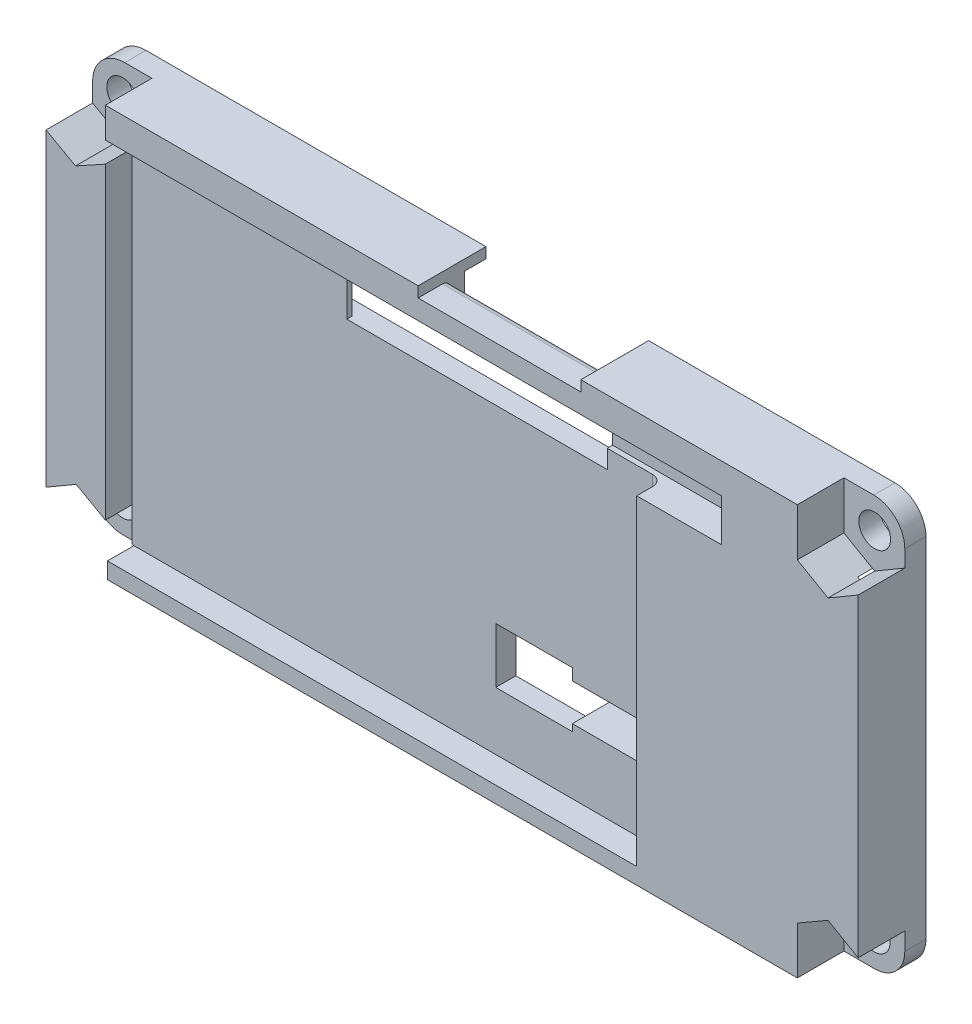
SolidWorks part; units mm, degrees
ref_plane "前视基准面" through (0, 0, 0) normal (0, 0, 1) x (1, 0, 0)
ref_plane "上视基准面" through (0, 0, 0) normal (0, 1, 0) x (1, 0, 0)
ref_plane "右视基准面" through (0, 0, 0) normal (1, 0, 0) x (0, 0, -1)
other "Configuration Table"
sketch "草图1" plane through (0, 0, 0) normal (0, 0, 1) x (1, 0, 0)
  line L0 (-73.5331, 38.5954) -> (-64.5685, 38.5954)
  line L1 (-2.794, 38.5954) -> (-73.5331, 38.5954) construction
  line L2 (-64.5685, 38.5954) -> (-64.5685, 29.9954)
  line L3 (-64.5685, 29.9954) -> (-75.2685, 29.9954)
  line L4 (-75.2685, 29.9954) -> (-75.2685, 9.1857)
  line L5 (-75.2685, 9.1857) -> (-68.5685, 9.1857)
  line L6 (-68.5685, 9.1857) -> (-68.5685, -0.1143)
  line L7 (-73.7871, -0.1143) -> (-2.715, -0.1143) construction
  line L8 (-68.5685, -0.1143) -> (-73.7871, -0.1143)
  line L9 (-76.5685, 2.667) -> (-76.5685, 35.5601)
  line L10 (-20.3702, 38.5954) -> (-2.794, 38.5954)
  line L11 (0.1298, 35.6715) -> (0.1298, 2.7305)
  line L12 (-2.715, -0.1143) -> (-29.3702, -0.1143)
  line L13 (-29.3702, -0.1143) -> (-29.3702, 7.5643)
  line L14 (-29.3702, 16.2857) -> (-25.7194, 16.2857)
  line L15 (-25.7194, 16.2857) -> (-25.7194, 22.5541)
  line L16 (-25.7194, 22.5541) -> (-20.6222, 22.5541)
  line L18 (-20.6222, 22.5541) -> (-20.6222, 16.1031)
  line L19 (-20.6222, 16.1031) -> (-21.974, 16.1031)
  line L21 (-21.974, 15.9031) -> (-21.974, 16.1031) construction
  line L22 (-21.974, 11.903) -> (-21.353, 11.903)
  line L23 (-21.353, 11.903) -> (-21.353, 11.0605)
  line L24 (-21.353, 2.6963) -> (-7.7837, 2.6963)
  line L25 (-7.7837, 2.6963) -> (-7.7837, 2.0822)
  line L26 (-7.7837, 2.0822) -> (-5.4155, 2.0822)
  line L27 (-5.4155, 2.0822) -> (-5.4155, 6.7277)
  line L28 (-5.4155, 6.7277) -> (-4.9394, 6.7277)
  line L29 (-4.9394, 6.7277) -> (-4.9394, 11.903)
  line L30 (-4.9394, 11.903) -> (-1.774, 11.903)
  line L31 (-1.774, 11.903) -> (-1.774, 30.5031)
  line L32 (-1.774, 29.9031) -> (-1.774, 12.003) construction
  line L33 (-3.774, 30.5031) -> (-1.774, 30.5031) construction
  line L34 (-5.774, 30.5031) -> (-5.774, 29.9954)
  line L35 (-5.774, 29.9954) -> (-20.3702, 29.9954)
  line L36 (-20.3702, 29.9954) -> (-20.3702, 38.5954)
  line L37 (-1.774, 12.003) -> (-20.374, 12.003) construction
  line L38 (-29.3702, 11.0605) -> (-29.3702, 16.2857)
  line L39 (-29.3702, 11.0605) -> (-21.353, 11.0605)
  line L41 (-29.3702, 7.5643) -> (-21.353, 7.5643)
  line L43 (-21.353, 7.5643) -> (-21.353, 2.6963)
  line L44 (-55.997, 25.7616) -> (-51.8906, 25.7616)
  line L45 (-55.997, 25.7616) -> (-55.997, 9.6668)
  line L46 (-55.997, 9.6668) -> (-51.8906, 9.6668)
  line L47 (-51.8906, 25.7616) -> (-51.8906, 9.6668)
  arc A0 (-73.7871, -0.1143) -> (-76.5685, 2.667) centre (-73.7871, 2.667) cw
  arc A1 (-76.5685, 35.5601) -> (-73.5331, 38.5954) centre (-73.5331, 35.5601) cw
  circle A2 centre (-73.7292, 35.7671) radius 1.5
  circle A3 centre (-73.7292, 2.755) radius 1.5
  arc A4 (-2.794, 38.5954) -> (0.1298, 35.6715) centre (-2.794, 35.6715) cw
  arc A5 (0.1298, 2.7305) -> (-2.715, -0.1143) centre (-2.715, 2.7305) cw
  arc A6 (-21.974, 16.1031) -> (-21.974, 11.903) centre (-21.974, 14.0031) ccw
  arc A7 (-1.774, 30.5031) -> (-5.774, 30.5031) centre (-3.774, 30.5031) ccw
  circle A8 centre (-21.974, 14.0031) radius 0.9 construction
  arc A9 (-3.5047, 29.8031) -> (-4.0433, 29.8031) centre (-3.774, 30.5031) ccw construction
  dimension "D1" = 8
  dimension "D2" = 9.3
  dimension "D3" = 1.3
  dimension "D4" = 8.6
  dimension "D5" = 12
  dimension "D6" = 0.1
  dimension "D7" = 0.1
  dimension "D8" = 20.5
  dimension "D9" = 29.5
extrude "凸台-拉伸1" add sketch "草图1" along normal blind 2
sketch "草图2" plane through (0, 0, 2) normal (0, 0, 1) x (1, 0, 0)
  line L0 (-20.3702, 38.5954) -> (-5.6189, 38.5954)
  line L1 (-2.794, 38.5954) -> (-20.3702, 38.5954) construction
  line L2 (-5.6189, 38.5954) -> (-5.6189, 34.0838)
  line L3 (-5.6189, 34.0838) -> (-2.7217, 32.4163)
  line L4 (-2.7217, 32.4163) -> (0.1298, 34.0838)
  line L5 (0.1298, 2.7305) -> (0.1298, 35.6715) construction
  line L6 (0.1298, 34.0838) -> (0.1298, 4.4128)
  line L7 (0.1298, 4.4128) -> (-2.7217, 6.054)
  line L8 (-2.7217, 6.054) -> (-5.6202, 4.3805)
  line L9 (-5.6202, 4.3805) -> (-5.6202, -0.1143)
  line L10 (-29.3702, -0.1143) -> (-2.715, -0.1143) construction
  line L11 (-5.6202, -0.1143) -> (-29.3702, -0.1143)
  line L12 (-29.3702, -0.1143) -> (-29.3702, 7.5643)
  line L13 (-29.3702, 7.5643) -> (-21.353, 7.5643)
  line L21 (-4.9394, 11.903) -> (-1.774, 11.903)
  line L22 (-1.774, 11.903) -> (-1.774, 30.5031)
  line L23 (-5.774, 30.5031) -> (-5.774, 29.9954)
  line L24 (-5.774, 29.9954) -> (-20.3702, 29.9954)
  line L25 (-20.3702, 29.9954) -> (-20.3702, 38.5954)
  line L26 (-21.353, 7.5643) -> (-20.7496, 7.5643)
  line L27 (-16.9173, 11.3967) -> (-16.9173, 11.903)
  line L28 (-16.9173, 11.903) -> (-4.9394, 11.903)
  line L29 (-70.8876, 38.5954) -> (-41.4286, 38.5954)
  line L30 (-64.5685, 38.5954) -> (-73.5331, 38.5954) construction
  line L31 (-2.794, 38.5954) -> (-73.5331, 38.5954) construction
  line L32 (-41.4286, 38.5954) -> (-41.4286, 35.0718)
  line L33 (-41.4286, 35.0718) -> (-56.2862, 35.0718)
  line L34 (-60.684, 30.6739) -> (-60.684, 29.9954)
  line L35 (-60.684, 29.9954) -> (-64.5685, 29.9954)
  line L36 (-64.5685, 29.9954) -> (-75.2685, 29.9954)
  line L37 (-75.2685, 29.9954) -> (-75.2685, 9.1857)
  line L38 (-75.2685, 9.1857) -> (-68.5685, 9.1857)
  line L39 (-68.5685, 9.1857) -> (-68.5685, 11.7982)
  line L40 (-68.5685, 11.7982) -> (-55.997, 11.7982)
  line L41 (-55.997, 25.7616) -> (-55.997, 9.6668) construction
  line L42 (-55.997, 11.7982) -> (-55.997, 25.7616)
  line L43 (-55.997, 25.7616) -> (-51.8906, 25.7616)
  line L44 (-51.8906, 25.7616) -> (-51.8906, 29.9954)
  line L45 (-51.8906, 29.9954) -> (-21.1628, 29.9954)
  line L46 (-21.1628, 29.9954) -> (-20.6222, 29.369)
  line L47 (-20.6222, 29.369) -> (-20.6222, 22.5541)
  line L48 (-20.6222, 22.5541) -> (-20.6222, 16.1031)
  line L49 (-20.6222, 16.1031) -> (-21.974, 16.1031)
  line L50 (-21.974, 11.903) -> (-21.353, 11.903)
  line L51 (-21.353, 11.0605) -> (-29.3702, 11.0605)
  line L52 (-29.3702, 11.0605) -> (-29.3702, 12.1441)
  line L53 (-29.3702, 16.2857) -> (-29.3702, 11.0605) construction
  line L54 (-29.3702, 12.1441) -> (-36.5981, 12.1441)
  line L55 (-36.5981, 12.1441) -> (-36.5981, -0.1143)
  line L56 (-73.7871, -0.1143) -> (-2.715, -0.1143) construction
  line L57 (-36.5981, -0.1143) -> (-70.7703, -0.1143)
  line L58 (-73.7871, -0.1143) -> (-68.5685, -0.1143) construction
  line L59 (-70.7703, -0.1143) -> (-70.7703, 4.5479)
  line L60 (-70.7703, 4.5479) -> (-73.7193, 6.209)
  line L61 (-73.7193, 6.209) -> (-76.5685, 4.5479)
  line L62 (-76.5685, 35.5601) -> (-76.5685, 2.667) construction
  line L63 (-76.5685, 4.5479) -> (-76.5685, 33.7734)
  line L64 (-76.5685, 33.7734) -> (-73.7871, 32.2146)
  line L65 (-73.7871, 32.2146) -> (-70.9685, 33.7734)
  line L66 (-70.9685, 34.5954) -> (-70.9685, 2.5954) construction
  line L67 (-70.9685, 33.7734) -> (-70.9685, 38.5954)
  line L68 (-70.9685, 38.5954) -> (-70.8876, 38.5954)
  line L69 (-21.353, 11.903) -> (-21.353, 11.0605)
  arc A0 (-1.774, 30.5031) -> (-5.774, 30.5031) centre (-3.774, 30.5031) ccw
  arc A1 (-20.7496, 7.5643) -> (-16.9173, 11.3967) centre (-20.7496, 11.3967) ccw
  arc A2 (-56.2862, 35.0718) -> (-60.684, 30.6739) centre (-56.2862, 30.6739) ccw
  arc A3 (-21.974, 16.1031) -> (-21.974, 11.903) centre (-21.974, 14.0031) ccw
extrude "凸台-拉伸2" add sketch "草图2" along normal blind 1.4
sketch "草图3" plane through (0, 0, 3.4) normal (0, 0, 1) x (1, 0, 0)
  line L0 (-20.3702, 38.5954) -> (-20.3702, 29.9954)
  line L2 (-20.6222, 29.369) -> (-21.1628, 29.9954)
  line L3 (-21.1628, 29.9954) -> (-26.0622, 29.9954)
  line L4 (-21.1628, 29.9954) -> (-51.8906, 29.9954) construction
  line L5 (-26.0622, 29.9954) -> (-26.0622, 38.5954)
  line L6 (-2.794, 38.5954) -> (-73.5331, 38.5954) construction
  line L7 (-26.0622, 38.5954) -> (-20.3702, 38.5954)
  line L8 (-20.6222, 29.369) -> (-20.6222, 29.9954)
  line L9 (-20.6222, 29.9954) -> (-20.3702, 29.9954)
  line L10 (-29.3702, 7.5643) -> (-29.3702, -0.1143) construction
  line L11 (-29.3702, 6.9117) -> (-36.5981, 6.9117)
  line L12 (-29.3702, 6.9117) -> (-29.3702, -0.1143)
  line L13 (-29.3702, -0.1143) -> (-36.5981, -0.1143)
  line L14 (-36.5981, 6.9117) -> (-36.5981, -0.1143)
  line L15 (-72.9367, 9.1857) -> (-75.2685, 9.1857)
  line L16 (-68.5685, 9.1857) -> (-75.2685, 9.1857) construction
  line L17 (-75.2685, 9.1857) -> (-75.2685, 11.4031)
  line L19 (-68.5685, 11.7982) -> (-70.86, 11.7982)
  line L21 (-70.86, 11.4031) -> (-70.86, 11.7982)
  line L22 (-68.5685, 11.7982) -> (-68.5685, 9.1857)
  line L23 (-68.5685, 9.1857) -> (-72.9367, 9.1857)
  line L26 (-75.2685, 11.4031) -> (-75.2685, 11.7982)
  line L27 (-75.2685, 11.7982) -> (-75.0082, 11.7982)
  line L28 (-75.0082, 11.4031) -> (-75.0082, 11.7982)
  line L29 (-51.8906, 29.9954) -> (-51.8906, 25.7616) construction
  line L30 (-51.8906, 27.9031) -> (-51.8906, 25.7616)
  line L31 (-51.8906, 25.7616) -> (-54.5706, 25.7616)
  line L32 (-51.8906, 25.7616) -> (-55.997, 25.7616) construction
  line L35 (-52.4222, 27.9031) -> (-52.4222, 29.9954)
  line L36 (-52.4222, 29.9954) -> (-51.8906, 29.9954)
  line L37 (-51.8906, 27.9031) -> (-51.8906, 29.9954)
  arc A1 (-75.0082, 11.4031) -> (-70.86, 11.4031) centre (-72.9341, 11.4031) ccw
  arc A2 (-73.2034, 12.1031) -> (-72.6649, 12.1031) centre (-72.9341, 11.4031) ccw construction
  arc A3 (-54.5706, 25.7616) -> (-52.4222, 27.9031) centre (-54.5706, 27.9101) ccw
extrude "凸台-拉伸3" add sketch "草图3" against normal blind 1.4
sketch "草图4" plane through (0, 0, 3.4) normal (0, 0, 1) x (1, 0, 0)
  circle A0 centre (-2.715, 35.7506) radius 1.5
  circle A1 centre (-2.7599, 2.755) radius 1.5
extrude "切除-拉伸1" cut sketch "草图4" against normal blind 4
sketch "草图5" plane through (0, 0, 3.4) normal (0, 0, 1) x (1, 0, 0)
  line L0 (-26.0622, 38.5954) -> (-5.6189, 38.5954)
  line L1 (-5.6189, 38.5954) -> (-5.6189, 34.0838)
  line L2 (-5.6189, 34.0838) -> (-2.7217, 32.4163)
  line L3 (-2.7217, 32.4163) -> (0.1298, 34.0838)
  line L4 (0.1298, 34.0838) -> (0.1298, 4.4128)
  line L5 (0.1298, 4.4128) -> (-2.7217, 6.054)
  line L6 (-2.7217, 6.054) -> (-5.6202, 4.3805)
  line L7 (-5.6202, 4.3805) -> (-5.6202, -0.1143)
  line L8 (-5.6202, -0.1143) -> (-70.7703, -0.1143)
  line L9 (-70.7703, -0.1143) -> (-70.7703, 1.4212)
  line L10 (-70.7703, 4.5479) -> (-70.7703, -0.1143) construction
  line L11 (-70.7703, 1.4212) -> (-20.7868, 1.4212)
  line L12 (-20.7868, 1.4212) -> (-20.7868, 35.7389)
  line L13 (-20.7868, 35.7389) -> (-70.9685, 35.7389)
  line L14 (-70.9685, 38.5954) -> (-70.9685, 33.7734) construction
  line L15 (-70.9685, 35.7389) -> (-70.9685, 38.5954)
  line L16 (-70.9685, 38.5954) -> (-26.0622, 38.5954)
  line L17 (-76.5685, 33.7734) -> (-73.7871, 32.2146)
  line L18 (-73.7871, 32.2146) -> (-70.9685, 33.7734)
  line L19 (-70.9685, 33.7734) -> (-70.9685, 4.6595)
  line L20 (-73.7193, 6.209) -> (-70.7703, 4.5479) construction
  line L21 (-70.9685, 34.5954) -> (-70.9685, 2.5954) construction
  line L22 (-70.9685, 4.6595) -> (-73.7193, 6.209)
  line L23 (-73.7193, 6.209) -> (-76.5685, 4.5479)
  line L24 (-76.5685, 4.5479) -> (-76.5685, 33.7734)
extrude "凸台-拉伸4" add sketch "草图5" along normal blind 3
sketch "草图6" plane through (0, 0, 6.4) normal (0, 0, 1) x (1, 0, 0)
  line L1 (-20.7868, 35.7389) -> (-12.7868, 35.7389)
  line L2 (-20.7868, 35.7389) -> (-20.7868, 31.7389)
  line L3 (-20.7868, 31.7389) -> (-12.7868, 31.7389)
  line L4 (-12.7868, 35.7389) -> (-12.7868, 31.7389)
  dimension "D1" = 4
  dimension "D2" = 8
extrude "切除-拉伸2" cut sketch "草图6" against normal blind 3
sketch "草图7" plane through (0, 0, 3.4) normal (0, 0, -1) x (-1, 0, 0)
  line L0 (41.4286, 35.0718) -> (41.4286, 38.5954) construction
  line L1 (26.0622, 38.5954) -> (41.4286, 38.5954)
  line L2 (26.0622, 38.5954) -> (26.0622, 37.5954)
  line L3 (26.0622, 37.5954) -> (41.4286, 37.5954)
  line L4 (41.4286, 38.5954) -> (41.4286, 37.5954)
  dimension "D1" = 1
extrude "切除-拉伸3" cut sketch "草图7" against normal blind 10
fillet "圆角1" radius 0.7 1 edges at (-33.7454, 37.5954, 3.4)
sketch "草图8" plane through (0, 0, 0) normal (0, 0, -1) x (-1, 0, 0)
  line L0 (5.774, 30.5031) -> (1.774, 30.5031) construction
  line L1 (3.774, 30.5031) -> (3.774, 32.5031) construction
  line L2 (21.974, 16.1031) -> (21.974, 11.903) construction
  line L3 (21.974, 14.0031) -> (24.074, 14.0031) construction
  line L4 (1.774, 30.5031) -> (1.774, 11.903) construction
  line L5 (5.974, 30.1954) -> (20.9222, 30.1954)
  line L6 (1.574, 30.2954) -> (1.574, 11.703)
  line L7 (1.574, 11.703) -> (20.9222, 11.703)
  line L8 (20.9222, 30.1954) -> (20.9222, 16.3031)
  line L9 (20.6222, 16.1031) -> (20.6222, 29.9954) construction
  line L10 (4.9394, 11.903) -> (16.9173, 11.903) construction
  line L11 (20.3702, 29.9954) -> (5.774, 29.9954) construction
  line L12 (1.574, 30.2954) -> (1.574, 30.5031)
  line L13 (5.974, 30.5031) -> (5.974, 30.1954)
  line L14 (20.9222, 16.3031) -> (21.974, 16.3031)
  line L15 (21.974, 11.703) -> (20.9222, 11.703)
  arc A0 (5.774, 30.5031) -> (1.774, 30.5031) centre (3.774, 30.5031) ccw construction
  arc A1 (21.974, 11.903) -> (21.974, 16.1031) centre (21.974, 14.0031) ccw construction
  arc A2 (1.574, 30.5031) -> (5.974, 30.5031) centre (3.774, 30.5031) cw
  arc A3 (5.774, 30.5031) -> (1.774, 30.5031) centre (3.774, 30.5031) ccw construction
  arc A4 (21.974, 16.3031) -> (21.974, 11.703) centre (21.974, 14.0031) cw
  dimension "D1" = 0.2
  dimension "D2" = 0.3
  dimension "D3" = 0.2
  dimension "D4" = 0.2
extrude "切除-拉伸4" cut sketch "草图8" against normal up to surface (3.4 mm away)
sketch "草图9" plane through (0, 0, 0) normal (0, 0, -1) x (-1, 0, 0)
  line L0 (55.997, 9.6668) -> (51.8906, 9.6668) construction
  line L1 (55.997, 25.7616) -> (55.797, 25.7616)
  line L2 (55.997, 25.7616) -> (55.997, 9.6668)
  line L3 (55.997, 9.6668) -> (55.797, 9.6668)
  line L4 (55.797, 25.7616) -> (55.797, 9.6668)
  dimension "D1" = 0.2
extrude "切除-拉伸5" cut sketch "草图9" against normal up to surface (2 mm away) up to face at (-55.7942, 34.13, 2)
sketch "草图10" plane through (0, 0, 2) normal (0, 0, -1) x (-1, 0, 0)
  line L0 (55.797, 25.7616) -> (55.797, 9.6668) construction
  line L1 (55.997, 25.7616) -> (55.797, 25.7616)
  line L2 (55.997, 25.7616) -> (55.997, 11.7982)
  line L3 (55.997, 11.7982) -> (55.797, 11.7982)
  line L4 (55.797, 25.7616) -> (55.797, 11.7982)
extrude "切除-拉伸6" cut sketch "草图10" against normal up to surface (1.4 mm away) up to face at (-38.0148, 16.8864, 3.4)
sketch "草图11" plane through (0, 0, 3.4) normal (0, 0, 1) x (1, 0, 0)
  line L0 (-20.7868, 1.4212) -> (-70.7703, 1.4212) construction
  line L1 (-70.9685, 35.7389) -> (-50.6639, 35.7389)
  line L2 (-70.9685, 35.7389) -> (-70.9685, 1.4212)
  line L3 (-70.9685, 1.4212) -> (-50.6639, 1.4212)
  line L4 (-50.6639, 35.7389) -> (-50.6639, 29.9954)
  line L10 (-26.0622, 29.9954) -> (-52.4222, 29.9954) construction
  line L11 (-20.7868, 31.7389) -> (-26.0622, 31.7389)
  line L12 (-20.7868, 31.7389) -> (-20.7868, 17.4736)
  line L14 (-26.0622, 31.7389) -> (-26.0622, 29.9954)
  line L17 (-26.0622, 29.9954) -> (-50.6639, 29.9954)
  line L20 (-29.3702, 12.1441) -> (-29.3702, 11.0605)
  line L23 (-50.6639, 1.4212) -> (-36.5981, 1.4212)
  line L24 (-36.5981, 12.1441) -> (-36.5981, 6.9117)
  line L27 (-36.5981, 12.1441) -> (-29.3702, 12.1441)
  line L29 (-29.3702, 6.9117) -> (-36.5981, 6.9117)
  line L31 (-29.3702, 1.4212) -> (-36.5981, 1.4212)
  line L33 (-29.3702, 7.5643) -> (-20.7868, 7.5643)
  line L34 (-29.3702, 7.5643) -> (-29.3702, 6.9117)
  line L35 (-29.3702, 1.4212) -> (-20.7868, 1.4212)
  line L36 (-20.7868, 7.5643) -> (-20.7868, 1.4212)
  line L37 (-29.3702, 11.0605) -> (-20.7868, 11.0605)
  line L38 (-20.7868, 31.7389) -> (-20.7868, 1.4212) construction
  line L39 (-20.7868, 11.0605) -> (-20.7868, 17.4736)
extrude "凸台-拉伸5" add sketch "草图11" along normal blind 0.5
fillet "圆角2" radius 1 2 edges at (-20.7868, 4.4927, 3.9) (-20.7868, 21.3997, 3.9)
sketch "草图12" plane through (0, 0, 2) normal (0, 0, -1) x (-1, 0, 0)
  line L0 (20.3702, 38.5954) -> (20.3702, 30.1954) construction
  line L1 (26.0622, 38.5954) -> (20.3702, 38.5954)
  line L2 (26.0622, 38.5954) -> (26.0622, 37.5954)
  line L3 (26.0622, 37.5954) -> (20.3702, 37.5954)
  line L4 (20.3702, 38.5954) -> (20.3702, 37.5954)
  line L5 (64.5685, 29.9954) -> (64.5685, 38.5954) construction
  line L6 (41.4286, 38.5954) -> (64.5685, 38.5954)
  line L7 (41.4286, 38.5954) -> (41.4286, 37.5954)
  line L8 (41.4286, 37.5954) -> (64.5685, 37.5954)
  line L9 (64.5685, 38.5954) -> (64.5685, 37.5954)
  dimension "D1" = 1
  dimension "D2" = 1
extrude "凸台-拉伸6" add sketch "草图12" along normal up to surface (2 mm away) up to face at (-9.8807, 15.0262, 0)
